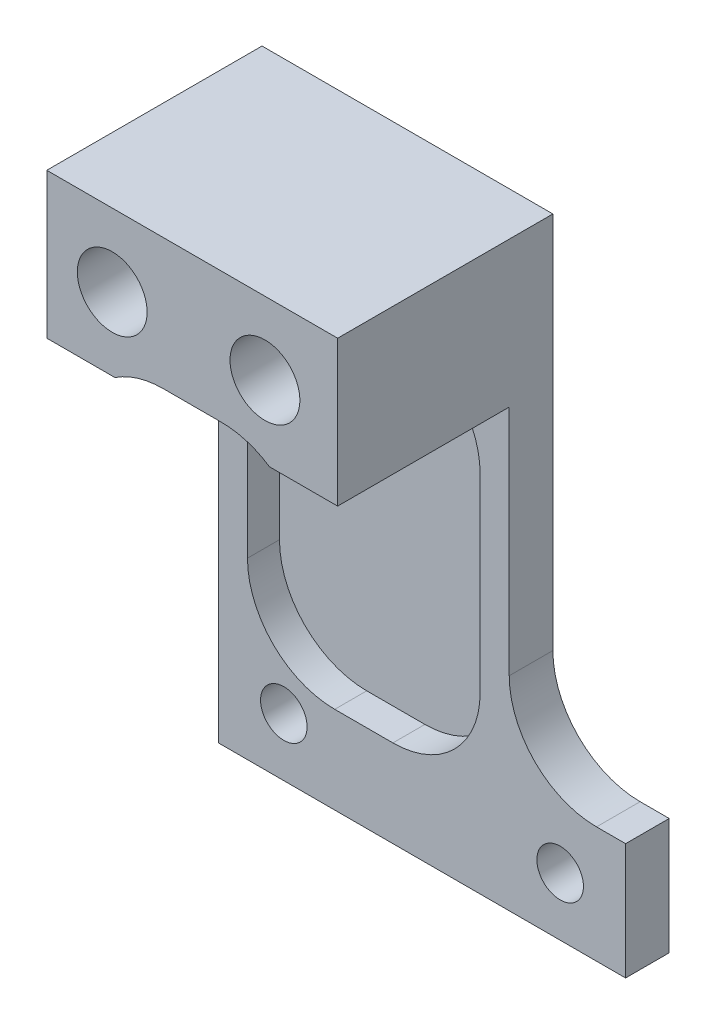
SolidWorks part; units mm, degrees
material "6061-T6 (SS)"
ref_plane "Front Plane" through (0, 0, 0) normal (0, 0, 1) x (1, 0, 0)
ref_plane "Top Plane" through (0, 0, 0) normal (0, 1, 0) x (1, 0, 0)
ref_plane "Right Plane" through (0, 0, 0) normal (1, 0, 0) x (0, 0, -1)
sketch "Sketch1" plane through (0, 0, 0) normal (0, 0, 1) x (1, 0, 0)
  line L0 (-4.75, -8) -> (4.75, -8) construction
  line L1 (7, -10) -> (-7, -10)
  line L2 (7, -10) -> (7, 10)
  line L3 (7, 10) -> (-7, 10)
  line L4 (-7, -10) -> (-7, 10)
  line L5 (7, -10) -> (-7, 10) construction
  line L6 (7, 10) -> (-7, -10) construction
  line L7 (0, 10) -> (0, -8) construction
  line L9 (-4.75, 10) -> (4.75, 10)
  line L10 (-4.75, 10) -> (-4.75, 7.5) construction
  line L11 (-4.75, 7.5) -> (4.75, 7.5) construction
  line L12 (4.75, 10) -> (4.75, 7.5) construction
  point P0 (0, 0)
  point P10 (0, -8)
  dimension "D1" = 14
  dimension "D2" = 20
  dimension "D3" = 2
  dimension "D4" = 9.5
  dimension "D5" = 2.5
extrude "Boss-Extrude1" add sketch "Sketch1" along normal blind 1.5 contours L4 L1 L2 L3
sketch "Sketch2" plane through (0, 0, 1.5) normal (0, 0, 1) x (1, 0, 0)
  line L0 (-7, -10) -> (-7, 10) construction
  line L1 (7, 10) -> (-7, 10)
  line L2 (7, 10) -> (7, 5)
  line L3 (7, 5) -> (-7, 5)
  line L4 (-7, 10) -> (-7, 5)
  dimension "D1" = 5
extrude "Boss-Extrude2" add sketch "Sketch2" along normal blind 5.9
hole_wizard "M2 Tapped Hole1" positions "3DSketch2" profile "Sketch5" tap size "M2" standard "ISO"
sketch3d "3DSketch2"
  point P8 (-4.75, -8, 0)
  point P10 (4.75, -8, 0)
sketch "Sketch5" plane through (-4.75, -8, 0) normal (1, 0, 0) x (0, 1, 0)
  line L0 (0, 0) -> (0, 6.4807)
  line L1 (0, 6.4807) -> (0.8, 6)
  line L2 (0.8, 6) -> (0.8, 0)
  line L5 (0.8, 0) -> (0, 0)
  line L10 (0, 6.4807) -> (-0.8, 6) construction
  line L11 (0, -6.35) -> (0, 107.95) construction
  dimension "Tap Drill Dia." = 1.6
  dimension "Tap Drill Depth" = 6
  dimension "Drill Angle" = 118
sketch "Sketch11" plane through (0, 0, 7.4) normal (0, 0, 1) x (1, 0, 0)
  line L0 (7, 10) -> (-7, 10) construction
  line L1 (7, -6) -> (6, -6)
  line L2 (7, -6) -> (7, 10)
  line L3 (7, 10) -> (3, 10)
  line L4 (3, -3) -> (3, 10)
  line L5 (7, 5) -> (7, 10) construction
  line L6 (7, -10) -> (-7, -10) construction
  arc A0 (6, -6) -> (3, -3) centre (6, -3) cw
  dimension "D3" = 3
  dimension "D1" = 4
  dimension "D2" = 4
extrude "Cut-Extrude6" cut sketch "Sketch11" against normal through all
sketch "Sketch12" plane through (0, 0, 0) normal (0, 0, -1) x (-1, 0, 0)
  line L0 (4.75, 7.5) -> (-0.5, 7.5) construction
  line L1 (-3, 10) -> (-3, -3) construction
  point P0 (4.75, 7.5)
  dimension "D1" = 2.5
hole_wizard "CBORE for M2 Hex Socket Head Cap Screw1" positions "3DSketch3" profile "Sketch13" counterbore size "M2" standard "ISO"
sketch3d "3DSketch3"
  point P0 (-4.75, 7.5, 0)
  point P3 (0.5, 7.5, 0)
sketch "Sketch13" plane through (-4.75, 7.5, 0) normal (1, 0, 0) x (0, 1, 0)
  line L0 (0, 0) -> (0, 8.221)
  line L1 (0, 8.221) -> (1.2, 7.5)
  line L2 (1.2, 7.5) -> (1.2, 2.4)
  line L3 (1.2, 2.4) -> (2.2, 2.4)
  line L4 (2.2, 2.4) -> (2.2, 0)
  line L5 (2.2, 0) -> (0, 0)
  line L10 (0, 8.221) -> (-1.2, 7.5) construction
  line L11 (0, -6.35) -> (0, 107.95) construction
  dimension "Hole Dia." = 2.4
  dimension "Hole Depth" = 7.5
  dimension "C'Bore Dia." = 4.4
  dimension "C'Bore Depth" = 2.4
  dimension "Drill Angle" = 118
sketch "Sketch14" plane through (0, 0, 7.4) normal (0, 0, 1) x (1, 0, 0)
  line L0 (-7, -10) -> (-7, 5) construction
  line L1 (-3, 5.5) -> (-1, 5.5)
  line L2 (-6, 2.5) -> (-6, -4)
  line L3 (-3, -7) -> (-1, -7)
  line L4 (2, 2.5) -> (2, -4)
  line L5 (3, 5) -> (3, -3) construction
  line L7 (-7, 5) -> (3, 5) construction
  line L8 (7, -10) -> (-7, -10) construction
  arc A0 (-3, 5.5) -> (-6, 2.5) centre (-3, 2.5) ccw
  arc A1 (-1, 5.5) -> (2, 2.5) centre (-1, 2.5) cw
  arc A2 (-6, -4) -> (-3, -7) centre (-3, -4) ccw
  arc A3 (-1, -7) -> (2, -4) centre (-1, -4) ccw
  dimension "D5" = 3
  dimension "D1" = 1
  dimension "D2" = 1
  dimension "D3" = 0.5
  dimension "D4" = 3
extrude "Cut-Extrude7" cut sketch "Sketch14" against normal blind 7
equation "\"D2@Sketch14\"=\"D1@Sketch14\""
